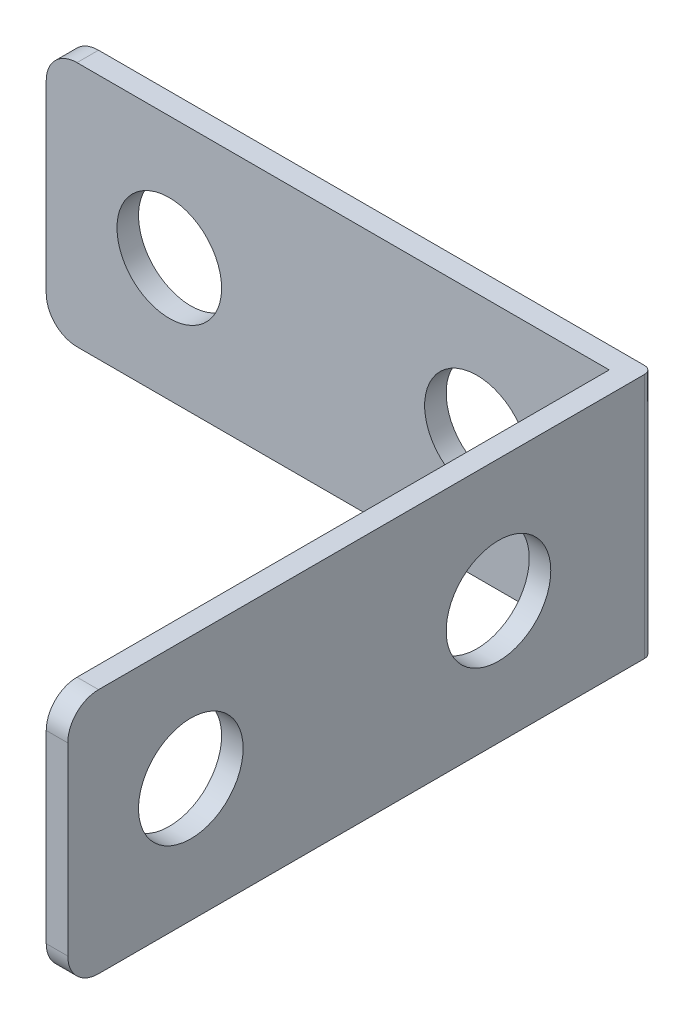
SolidWorks part; units mm, degrees
ref_plane "前视基准面" through (0, 0, 0) normal (0, 0, 1) x (1, 0, 0)
ref_plane "上视基准面" through (0, 0, 0) normal (0, 1, 0) x (1, 0, 0)
ref_plane "右视基准面" through (0, 0, 0) normal (1, 0, 0) x (0, 0, -1)
sketch "草图1" plane through (0, 0, 0) normal (0, 0, 1) x (1, 0, 0)
  line L1 (-9.5, -4) -> (9.5, -4)
  line L2 (-9.5, -4) -> (-9.5, 4)
  line L3 (-9.5, 4) -> (9.5, 4)
  line L4 (9.5, -4) -> (9.5, 4)
  line L5 (-9.5, -4) -> (9.5, 4) construction
  line L6 (-9.5, 4) -> (9.5, -4) construction
  circle A0 centre (-5.5, 0) radius 1.7
  circle A1 centre (4.5, 0) radius 1.7
  point P0 (0, 0)
extrude "凸台-拉伸1" add sketch "草图1" along normal blind 0.7
sketch "草图2" plane through (9.5, 0, 0) normal (1, 0, 0) x (0, 0, -1)
  line L0 (0, 4) -> (0, -4)
  line L1 (0, 4) -> (-19, 4)
  line L2 (0, -4) -> (-19, -4)
  line L3 (-19, 4) -> (-19, -4)
  circle A0 centre (-5, 0) radius 1.7
  circle A1 centre (-15, 0) radius 1.7
extrude "凸台-拉伸2" add sketch "草图2" against normal blind 0.7
fillet "圆角1" radius 1 4 edges at (-9.5, -4, 0.35) (-9.5, 4, 0.35) (9.15, 4, 19) (9.15, -4, 19)
fillet "圆角2" radius 0.25 1 edges at (9.5, 0, 0)
